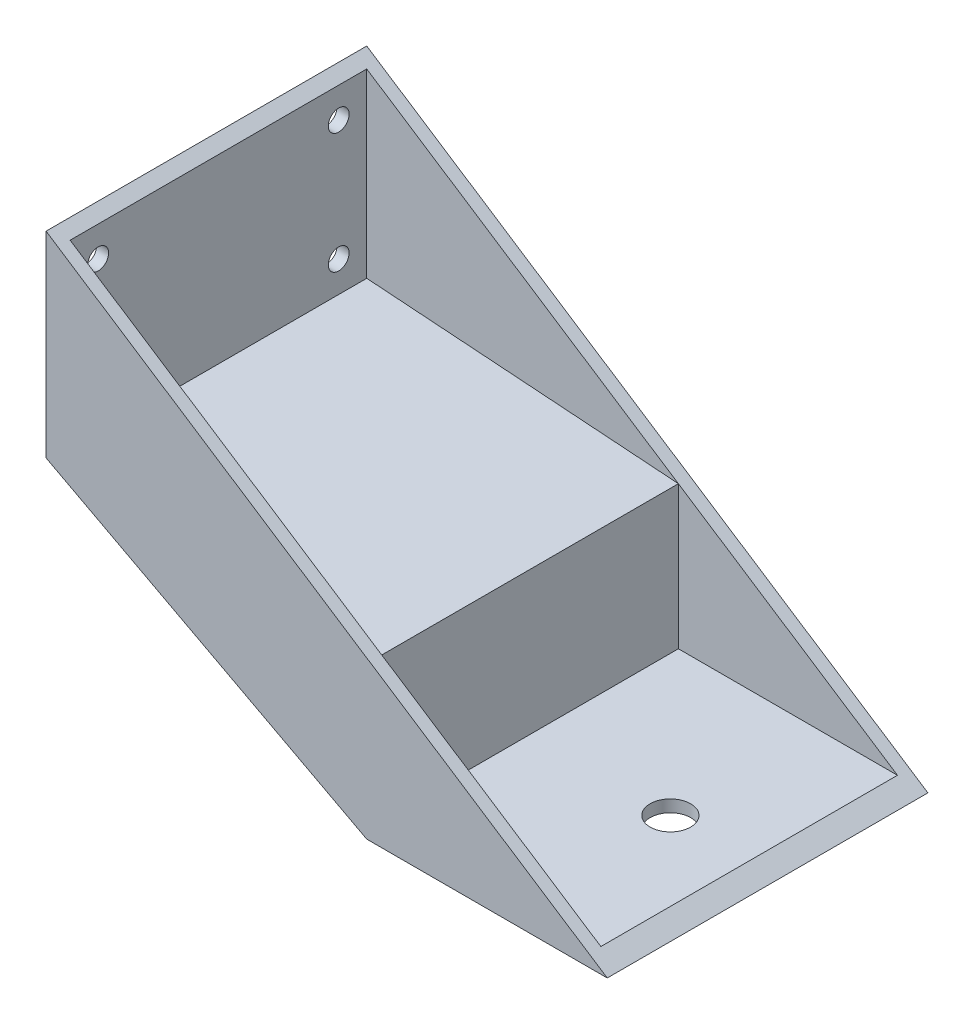
SolidWorks part; units mm, degrees
ref_plane "前视基准面" through (0, 0, 0) normal (0, 0, 1) x (1, 0, 0)
ref_plane "上视基准面" through (0, 0, 0) normal (0, 1, 0) x (1, 0, 0)
ref_plane "右视基准面" through (0, 0, 0) normal (1, 0, 0) x (0, 0, -1)
other "Configuration Table"
sketch "草图5" plane through (0, 0, 0) normal (0, 0, 1) x (1, 0, 0)
  line L0 (0, 49) -> (0, 0)
  line L1 (0, 0) -> (80, -42.3597)
  line L3 (80, -42.3597) -> (140, -42.3597)
  line L4 (140, -42.3597) -> (0, 49)
  point P3 (155.0609, -42.3597)
  dimension "D1" = 42.3597
  dimension "D2" = 80
  dimension "D3" = 49
  dimension "D4" = 60
extrude "凸台-拉伸3" add sketch "草图5" along normal blind 80
shell "抽壳14" thickness 3
sketch "草图9" plane through (0, 0, 0) normal (-1, 0, 0) x (0, 0, 1)
  line L0 (40, 49) -> (40, 0) construction
  line L1 (80, 49) -> (0, 49) construction
  line L2 (80, 0) -> (0, 0) construction
  circle A0 centre (70, 9.5) radius 2.6
  circle A1 centre (70, 39.5) radius 2.6
  circle A2 centre (10, 9.5) radius 2.6
  circle A3 centre (10, 39.5) radius 2.6
  dimension "D1" = 9.5
  dimension "D2" = 60
extrude "切除-拉伸1" cut sketch "草图9" against normal up to next contours A2 | A3 | A1 | A0
sketch "草图23" plane through (0, 0, 3) normal (0, 0, 1) x (1, 0, 0)
  line L0 (80.7452, -39.3597) -> (80.7452, -3.6919)
  line L6 (135.4028, -39.3597) -> (3, 47.0423) construction
  line L8 (3, 1.8061) -> (80.7452, -3.6919)
  line L9 (3, 1.8061) -> (80.7452, -39.3597)
extrude "凸台-拉伸7" add sketch "草图23" along normal up to next
sketch "草图24" plane through (0, -39.3597, 0) normal (0, 1, 0) x (1, 0, 0)
  line L0 (80.7452, -40) -> (135.4028, -40) construction
  line L1 (80.7452, -77) -> (80.7452, -3) construction
  line L2 (135.4028, -77) -> (135.4028, -3) construction
  circle A0 centre (115.7452, -40) radius 5.05
  point P10 (80.7452, -40.6352)
  point P11 (105.4738, -66.1089)
  point P14 (112.369, -50.4885)
extrude "切除-拉伸2" cut sketch "草图24" against normal up to next
